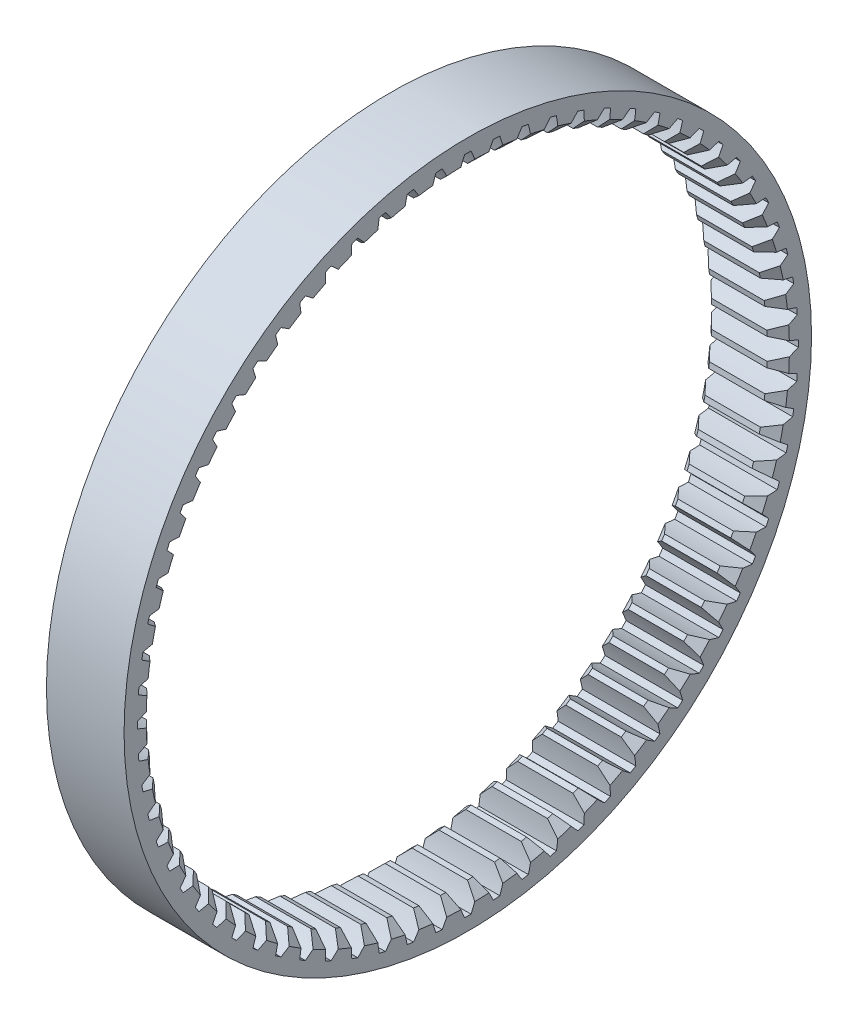
SolidWorks part; units mm, degrees
ref_plane "Plane1" through (0, 0, 0) normal (0, 0, 1) x (1, 0, 0)
ref_plane "Plane2" through (0, 0, 0) normal (0, 1, 0) x (1, 0, 0)
ref_plane "Plane3" through (0, 0, 0) normal (1, 0, 0) x (0, 0, -1)
other "Configuration Table"
sketch "HoldingSke" plane through (0, 0, 0) normal (0, 1, 0) x (1, 0, 0)
  line L0 (0, 0) -> (0.3863, -1.1888)
  line L1 (-15, 0) -> (100, 0) construction
  line L2 (0, 0) -> (-2.1039, 2.3779)
  line L3 (0, 0) -> (-11.863, 4.5341)
  line L4 (0, 0) -> (2.6687, 8.2133)
  line L5 (0, 0) -> (-23.7986, -8.8762)
  line L6 (0, 0) -> (-10.5278, -7.1032)
  line L7 (-2.1039, 2.3779) -> (3.3635, 27.1825)
  line L8 (-76.2, 3.1779) -> (-54.61, 3.1779)
  line L9 (-71.009, 38.7566) -> (-53.1078, 45.2721)
  line L10 (-76.2, 71.12) -> (104.1128, 71.12)
  line L11 (0, 0) -> (-7, 0)
  line L12 (-76.2, 101.6) -> (-76.17, 101.6)
  line L13 (24.9733, 27.94) -> (52.9518, 28.4284)
  line L14 (24.9733, 27.94) -> (24.9743, 27.94)
  line L15 (24.9733, 27.94) -> (100.4006, 29.5858)
  circle A0 centre (0, 0) radius 31
  circle A1 centre (0, 0) radius 12.7
  circle A2 centre (0, 0) radius 12.7
  dimension "MHD" = 25.4
  dimension "Hub_dia" = 25.4
  dimension "Diameter" = 62
  dimension "Num_teeth" = 72
  dimension "Pitch" = 1.25
  dimension "Overall_len" = 25.4
  dimension "Show_teeth" = 72
  dimension "Thickness" = 12.7
  dimension "OAL" = 25.4001
  dimension "T_dim" = 21.59
  dimension "Ap" = 20
  dimension "H" = 19.05
  dimension "Pitch_radius" = 180.3128
  dimension "Width" = 7
  dimension "Backlash" = 0.03
  dimension "Addendum_fac" = 1
  dimension "Dedendum_fac" = 1.25
  dimension "Clearance_fac" = 0.25
  dimension "Dedendum_add" = 0.001
  dimension "Module" = 0.8
sketch "BasProSke" plane through (0, 0, 0) normal (0, 1, 0) x (1, 0, 0)
  line L0 (-10, 0) -> (60, 0) construction
  line L1 (0, 28) -> (0, 31)
  line L2 (0, 28) -> (7, 28)
  line L3 (7, 28) -> (7, 31)
  line L4 (7, 31) -> (0, 31)
  dimension "Diameter" = 62
  dimension "Thickness" = 7
  dimension "Inside_diameter" = 56
revolve "Base-Revolve" add sketch "BasProSke" angle 360 about L0
sketch "TooCutSke" plane through (0, 0, 0) normal (1, 0, 0) x (0, 0, -1)
  line L3 (0.7033, 28.7914) -> (0.7033, 53.6633) construction
  line L4 (0, 0) -> (0, 59.563) construction
  line L5 (0, 0) -> (-2.9804, 68.2625) construction
  line L6 (-12.8116, 23.8207) -> (36.7444, 25.9843) construction
  circle A0 centre (0, 0) radius 28.8 construction
  circle A1 centre (0, 0) radius 29.801 construction
  circle A2 centre (0, 0) radius 24.3568 construction
  circle A3 centre (0, 0) radius 27.9746 construction
  arc A4 (0.9814, 27.9574) -> (0.2885, 29.7996) centre (-12.8116, 23.8207) ccw
  arc A5 (0.9814, 27.9574) -> (-0.9814, 27.9574) centre (0, 0) ccw
  arc A6 (0.2885, 29.7996) -> (-0.2885, 29.7996) centre (0, 0) ccw
  arc A7 (-0.2885, 29.7996) -> (-0.9814, 27.9574) centre (12.8116, 23.8207) ccw
  dimension "Pitch_dia" = 57.6
  dimension "Base_dia" = 48.7137
  dimension "Root_dia" = 59.602
  dimension "Overcut_dia" = 55.9492
  dimension "Flank_rad" = 14.4
  dimension "Half_ang" = 2.5
  dimension "Half_CT" = 0.7033
extrude "ToothCut" cut sketch "TooCutSke" along normal through all
fillet "Breaks" [suppressed] radius 0.08
fillet "RootFillets" [suppressed] radius 0.201
pattern_circular "TeethCuts" count 72 every 5 about axis through (-10, 0, 0) along (1, 0, 0) of "RootFillets", "Breaks", "ToothCut"
sketch "Szkic1" plane through (0, 0, 0) normal (0, 1, 0) x (1, 0, 0)
  line L0 (0, -29) -> (0, -28)
  line L1 (0, 31) -> (0, -31) construction
  line L2 (0, -28) -> (1, -28)
  line L3 (1, -28) -> (0, -29)
  point P6 (0, 0)
  dimension "D1" = 1
  dimension "D2" = 28
ref_axis "Oś1" through (7, 0, 0) along (-1, 0, 0)
revolve "Wycięcie-obrót1" cut sketch "Szkic1" angle 360 about axis through (7, 0, 0) along (-1, 0, 0)
ref_plane "Płaszczyzna1" through (3.5, 0, 0) normal (-1, 0, 0) x (0, 0, 1)
mirror "Lustro1" about plane through (3.5, 0, 0) normal (-1, 0, 0) of "Wycięcie-obrót1"
equation "' \"Module@HoldingSke\" = 6.35"
equation "' \"Num_teeth@HoldingSke\" = 24"
equation "' \"Ap@HoldingSke\" =  14.5"
equation "' \"Ap@HoldingSke\" = 14.5"
equation "' \"Width@HoldingSke\" = 12"
equation "' \"Diameter@HoldingSke\" = 8 * 25.4"
equation "' \"Show_teeth@HoldingSke\" = 100"
equation "' \"Backlash@HoldingSke\" = 0.009 * 25.4"
equation "' \"Addendum_fac@HoldingSke\" = 1.0"
equation "' \"Dedendum_fac@HoldingSke\" = 1.25"
equation "' \"Dedendum_add@HoldingSke\" = 0.00005 * 25.4"
equation "' \"Clearance_fac@HoldingSke\" = 0.25"
equation "\"Pitch@HoldingSke\" = 1 / \"Module@HoldingSke\" "
equation "\"Overcut_dia@TooCutSke\" = (\"Num_teeth@HoldingSke\" - 2 * \"Addendum_fac@HoldingSke\") / \"Pitch@HoldingSke\" - 0.002 * 25.4"
equation "\"Pitch_dia@TooCutSke\" = \"Num_teeth@HoldingSke\" / \"Pitch@HoldingSke\""
equation "\"Base_dia@TooCutSke\" = \"Num_teeth@HoldingSke\" / \"Pitch@HoldingSke\" * cos((\"Ap@HoldingSke\"  * 3.14159265 / 180)) * 0.90"
equation "\"Root_dia@TooCutSke\" = \"Num_teeth@HoldingSke\"  / \"Pitch@HoldingSke\" + 2 *  \"Dedendum_fac@HoldingSke\"/ \"Pitch@HoldingSke\" + \"Dedendum_add@HoldingSke\" * 2"
equation "\"Half_ang@TooCutSke\" = 180 / \"Num_teeth@HoldingSke\""
equation "\"Half_CT@TooCutSke\" = \"Num_teeth@HoldingSke\" / \"Pitch@HoldingSke\" * sin((3.14159265 / 2 / \"Num_teeth@HoldingSke\")) / 2 + 10 * \"Backlash@HoldingSke\" / 4"
equation "\"Flank_rad@TooCutSke\" = \"Num_teeth@HoldingSke\" / \"Pitch@HoldingSke\" / 4"
equation "\"Radius@RootFillets\"= \"Clearance_fac@HoldingSke\" / \"Pitch@HoldingSke\" + \"Dedendum_add@HoldingSke\""
equation "\"Break_rad@Breaks\" = 0.02 / \"Pitch@HoldingSke\" * 5"
equation "\"Num_teeth@TeethCuts\" = int( \"Show_teeth@HoldingSke\" ) + 1"
equation "\"Num_teeth@TeethCuts\" = ((sgn( \"Num_teeth@TeethCuts\" - \"Num_teeth@HoldingSke\" )-1)*( \"Num_teeth@TeethCuts\" - \"Num_teeth@HoldingSke\" ))/-2+ \"Num_teeth@HoldingSke\""
equation "\"Num_teeth@TeethCuts\" = ((sgn( \"Num_teeth@TeethCuts\" - 2.0)+1)*( \"Num_teeth@TeethCuts\" - 2.0))/2 +2.0"
equation "\"Angle@TeethCuts\" = 360.0 / \"Num_teeth@HoldingSke\""
equation "\"Diameter@BasProSke\" = \"Num_teeth@HoldingSke\"  / \"Pitch@HoldingSke\" + 2 *  \"Dedendum_fac@HoldingSke\"/ \"Pitch@HoldingSke\" + \"Dedendum_add@HoldingSke\" * 2 + 0.002 * 25.4"
equation "\"Diameter@BasProSke\" = ((sgn( \"Diameter@BasProSke\"  - \"Diameter@HoldingSke\" )+1)*( \"Diameter@BasProSke\"  - \"Diameter@HoldingSke\" ))/2 + \"Diameter@HoldingSke\""
equation "\"Inside_diameter@BasProSke\" =  (\"Num_teeth@HoldingSke\" - 2 * \"Addendum_fac@HoldingSke\") / \"Pitch@HoldingSke\" "
equation "\"Thickness@BasProSke\"  = \"Width@HoldingSke\""
